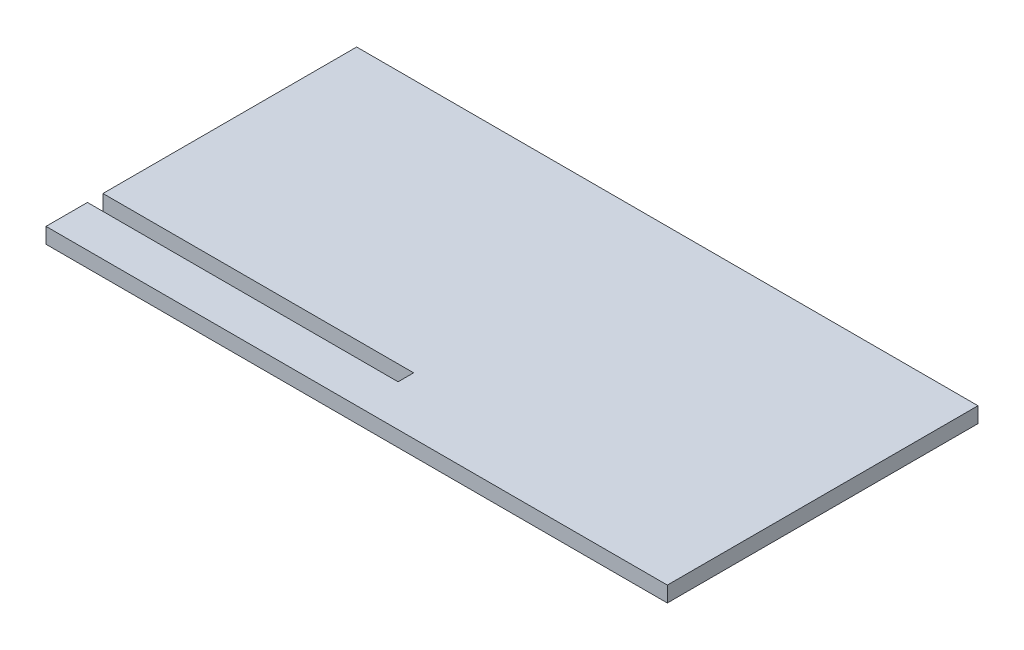
SolidWorks part; units mm, degrees
ref_plane "Front Plane" through (0, 0, 0) normal (0, 0, 1) x (1, 0, 0)
ref_plane "Top Plane" through (0, 0, 0) normal (0, 1, 0) x (1, 0, 0)
ref_plane "Right Plane" through (0, 0, 0) normal (1, 0, 0) x (0, 0, -1)
sketch "Sketch1" plane through (0, 0, 0) normal (0, 1, 0) x (1, 0, 0)
  line L0 (-60, -9) -> (0, -9)
  line L1 (-60, -20) -> (60, -20)
  line L2 (-60, -20) -> (-60, 40)
  line L3 (-60, 40) -> (60, 40)
  line L4 (60, -20) -> (60, 40)
  line L7 (0, -9) -> (0, -12)
  line L8 (0, -12) -> (-60, -12)
  point P0 (0, 0)
  dimension "D1" = 8
  dimension "D2" = 120
  dimension "D3" = 9
  dimension "D4" = 3
  dimension "D5" = 40
extrude "Boss-Extrude1" add sketch "Sketch1" along normal blind 3 contours L7 L8 L2 L1 L4 L3 L0
